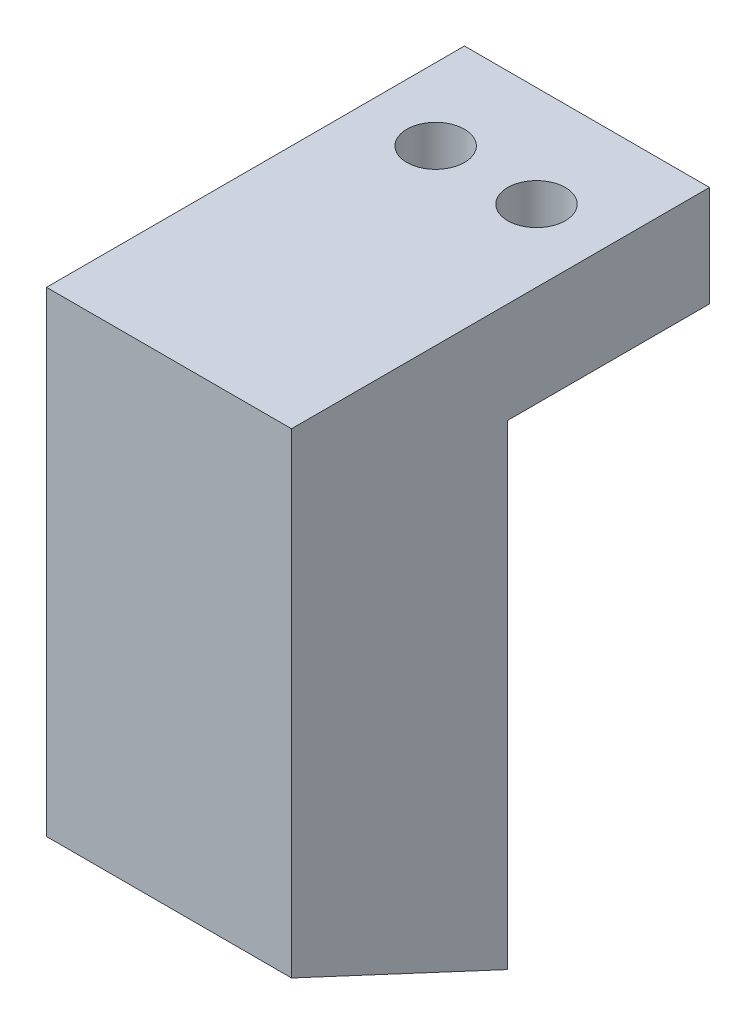
SolidWorks part; units mm, degrees
material "ABS"
ref_plane "Front Plane" through (0, 0, 0) normal (0, 0, 1) x (1, 0, 0)
ref_plane "Top Plane" through (0, 0, 0) normal (0, 1, 0) x (1, 0, 0)
ref_plane "Right Plane" through (0, 0, 0) normal (1, 0, 0) x (0, 0, -1)
sketch "Sketch1" plane through (0, 0, 0) normal (0, 1, 0) x (1, 0, 0)
  line L1 (-76.9048, 16.0714) -> (-59.9048, 16.0714)
  line L2 (-76.9048, 16.0714) -> (-76.9048, 1.0714)
  line L3 (-76.9048, 1.0714) -> (-59.9048, 1.0714)
  line L4 (-59.9048, 16.0714) -> (-59.9048, 1.0714)
  dimension "D1" = 15
  dimension "D2" = 17
extrude "Boss-Extrude1" add sketch "Sketch1" along normal blind 40
sketch "Sketch2" plane through (-59.9048, 0, 0) normal (1, 0, 0) x (0, 0, -1)
  line L3 (1.0714, 0) -> (16.0714, 0) construction
  line L5 (16.0714, 0) -> (1.0714, 0)
  line L6 (16.0714, 40) -> (16.0714, 0) construction
  line L7 (1.0714, 40) -> (1.0714, 0) construction
  line L8 (1.0714, 0) -> (1.0714, 6.9946)
  line L9 (1.0714, 6.9946) -> (16.0714, 0)
  dimension "D1" = 25
  dimension "D2" = 0
extrude "Cut-Extrude1" cut sketch "Sketch2" against normal blind 40
sketch "Sketch3" plane through (0, 6.1557, -2.8705) normal (0, -0.9063, 0.4226) x (1, 0, 0)
  line L0 (-76.9048, 1.985) -> (-59.9048, 1.985) construction
  line L2 (-59.9048, -14.5657) -> (-59.9048, 1.985) construction
  circle A0 centre (-68.3693, -5.515) radius 1.5
  point P4 (-68.4048, 1.985)
  point P7 (-59.9048, -6.2903)
  dimension "D1" = 7.5
  dimension "D2" = 8.5
  dimension "D3" = 3
extrude "Cut-Extrude2" cut sketch "Sketch3" against normal blind 36
sketch "Sketch4" plane through (0, 0, -16.0714) normal (0, 0, -1) x (-1, 0, 0)
  line L0 (59.9048, 40) -> (59.9048, 0) construction
  line L1 (76.9048, 40) -> (59.9048, 40)
  line L2 (76.9048, 40) -> (76.9048, 33)
  line L3 (76.9048, 33) -> (59.9048, 33)
  line L4 (59.9048, 40) -> (59.9048, 33)
  dimension "D1" = 7
extrude "Boss-Extrude2" add sketch "Sketch4" along normal blind 14
sketch "Sketch5" plane through (0, 33, 0) normal (0, -1, 0) x (-1, 0, 0)
  line L0 (59.9048, 30.0714) -> (76.9048, 30.0714) construction
  line L1 (59.9048, 30.0714) -> (59.9048, 16.0714) construction
  line L2 (76.9048, 30.0714) -> (76.9048, 16.0714) construction
  circle A0 centre (71.9048, 23.0714) radius 2
  circle A1 centre (64.9048, 23.0714) radius 2
  dimension "D1" = 4
  dimension "D2" = 4
  dimension "D3" = 7
  dimension "D4" = 5
  dimension "D5" = 5
  dimension "D6" = 7
extrude "Cut-Extrude3" cut sketch "Sketch5" against normal blind 14
